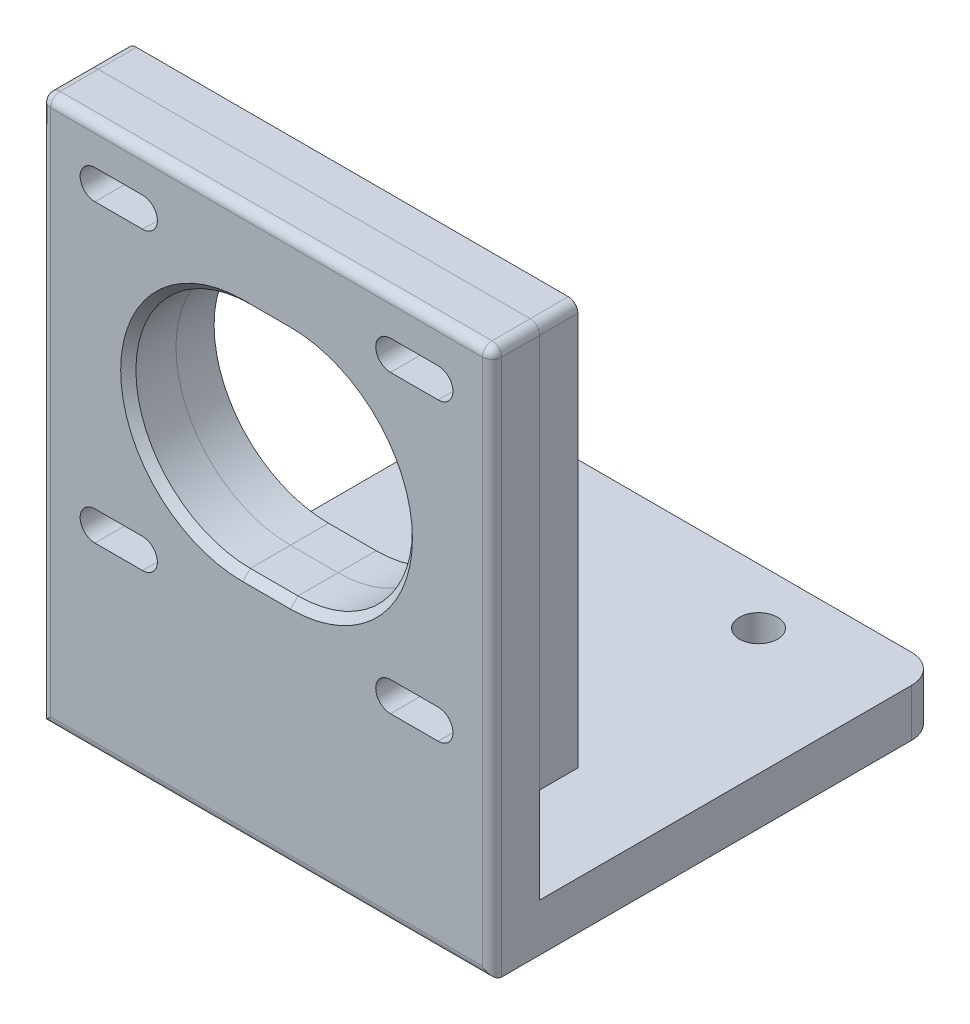
SolidWorks part; units mm, degrees
ref_plane "Front Plane" through (0, 0, 0) normal (0, 0, 1) x (1, 0, 0)
ref_plane "Top Plane" through (0, 0, 0) normal (0, 1, 0) x (1, 0, 0)
ref_plane "Right Plane" through (0, 0, 0) normal (1, 0, 0) x (0, 0, -1)
sketch "Sketch2" plane through (0, 0, 0) normal (1, 0, 0) x (0, 0, -1)
  line L0 (0, 0) -> (0, -47.3)
  line L4 (0, -47.3) -> (0, -52.3)
  line L5 (0, -52.3) -> (42, -52.3)
  line L6 (42, -52.3) -> (42, -57.3)
  line L7 (42, -57.3) -> (-5, -57.3)
  line L8 (-5, -57.3) -> (-5, 0)
  line L9 (-5, 0) -> (0, 0)
  dimension "D1" = 47.3
  dimension "D2" = 5
  dimension "D3" = 5
  dimension "D4" = 42
extrude "Boss-Extrude2" add sketch "Sketch2" along normal blind 47.3
sketch "Sketch3" plane through (0, 0, 5) normal (0, 0, 1) x (1, 0, 0)
  line L0 (21.15, -21.15) -> (26.15, -21.15) construction
  line L1 (21.15, -9.15) -> (26.15, -9.15)
  line L2 (21.15, -33.15) -> (26.15, -33.15)
  line L3 (0, -42.3) -> (47.3, -42.3) construction
  line L7 (0, 0) -> (0, -57.3) construction
  line L8 (5.65, -36.65) -> (10.65, -36.65) construction
  line L9 (5.65, -35.1) -> (10.65, -35.1)
  line L10 (5.65, -38.2) -> (10.65, -38.2)
  line L11 (47.3, 0) -> (47.3, -57.3) construction
  line L12 (47.3, 0) -> (0, 0) construction
  line L13 (23.65, -21.15) -> (50023.65, -21.15) construction
  line L16 (5.65, -7.2) -> (10.65, -7.2)
  line L19 (5.65, -4.1) -> (10.65, -4.1)
  line L22 (23.65, -42.3) -> (23.65, 0) construction
  line L23 (5.65, -5.65) -> (10.65, -5.65) construction
  line L24 (36.65, -7.2) -> (41.65, -7.2)
  line L25 (36.65, -4.1) -> (41.65, -4.1)
  line L26 (36.65, -5.65) -> (41.65, -5.65) construction
  line L27 (36.65, -38.2) -> (41.65, -38.2)
  line L28 (36.65, -35.1) -> (41.65, -35.1)
  line L29 (36.65, -36.65) -> (41.65, -36.65) construction
  arc A0 (21.15, -9.15) -> (21.15, -33.15) centre (21.15, -21.15) ccw
  arc A1 (26.15, -33.15) -> (26.15, -9.15) centre (26.15, -21.15) ccw
  arc A2 (5.65, -35.1) -> (5.65, -38.2) centre (5.65, -36.65) ccw
  arc A3 (10.65, -38.2) -> (10.65, -35.1) centre (10.65, -36.65) ccw
  arc A10 (5.65, -4.1) -> (5.65, -7.2) centre (5.65, -5.65) ccw
  arc A11 (10.65, -7.2) -> (10.65, -4.1) centre (10.65, -5.65) ccw
  arc A12 (36.65, -4.1) -> (36.65, -7.2) centre (36.65, -5.65) ccw
  arc A13 (41.65, -7.2) -> (41.65, -4.1) centre (41.65, -5.65) ccw
  arc A14 (36.65, -35.1) -> (36.65, -38.2) centre (36.65, -36.65) ccw
  arc A15 (41.65, -38.2) -> (41.65, -35.1) centre (41.65, -36.65) ccw
  point P2 (23.65, -21.15)
  point P15 (8.15, -36.65)
  point P30 (8.15, -5.65)
  point P37 (39.15, -5.65)
  point P44 (39.15, -36.65)
  dimension "D6" = 1.55
  dimension "D1" = 24
  dimension "D2" = 5
  dimension "D4" = 15.5
  dimension "D3" = 42.3
  dimension "D5" = 15.5
  dimension "D7" = 2
  dimension "D8" = 2
extrude "Cut-Extrude1" cut sketch "Sketch3" against normal up to next
fillet "Fillet1" radius 1 6 edges at (23.65, -57.3, 5) (47.3, -28.65, 5) (0, -28.65, 5) (23.65, 0, 5) (47.3, 0, 2.5) (0, 0, 2.5)
chamfer "Chamfer1" distance 0.8 angle 45 4 edges at (38.15, -21.15, 5) (23.65, -9.15, 5) (23.65, -33.15, 5) (9.15, -21.15, 5)
fillet "Fillet2" radius 3 2 edges at (47.3, -54.8, -42) (0, -54.8, -42)
sketch "Sketch4" plane through (0, -52.3, 0) normal (0, 1, 0) x (1, 0, 0)
  line L0 (9.65, 5) -> (37.65, 33) construction
  line L1 (44.3, 42) -> (3, 42) construction
  line L2 (9.65, 5) -> (37.65, 33) construction
  line L3 (9.65, 5) -> (34.0834, 36.161) construction
  circle A0 centre (9.65, 5) radius 2
  circle A1 centre (37.65, 33) radius 2 construction
  circle A2 centre (34.0834, 36.161) radius 2
  point P4 (23.65, 19)
  point P7 (23.65, 42)
  dimension "D1" = 4
  dimension "D2" = 4
  dimension "D4" = 28
  dimension "D5" = 28
  dimension "D3" = 5
  dimension "D7" = 6.9
  dimension "D6" = 2
extrude "Cut-Extrude2" cut sketch "Sketch4" against normal up to next
sketch "Sketch5" plane through (0, 0, 0) normal (0, 0, -1) x (-1, 0, 0)
  line L0 (-21.15, -9.15) -> (-26.15, -9.15) construction
  line L1 (-26.15, -33.15) -> (-21.15, -33.15) construction
  line L2 (-21.15, -9.15) -> (-26.15, -9.15)
  line L3 (-26.15, -33.15) -> (-21.15, -33.15)
  line L4 (-41.65, -7.2) -> (-36.65, -7.2) construction
  line L5 (-36.65, -4.1) -> (-41.65, -4.1) construction
  line L6 (-41.65, -38.2) -> (-36.65, -38.2) construction
  line L7 (-36.65, -35.1) -> (-41.65, -35.1) construction
  line L8 (-10.65, -38.2) -> (-5.65, -38.2) construction
  line L9 (-5.65, -35.1) -> (-10.65, -35.1) construction
  line L10 (-5.65, -4.1) -> (-10.65, -4.1) construction
  line L11 (-10.65, -7.2) -> (-5.65, -7.2) construction
  line L12 (-41.65, -7.2) -> (-36.65, -7.2)
  line L13 (-36.65, -4.1) -> (-41.65, -4.1)
  line L14 (-41.65, -38.2) -> (-36.65, -38.2)
  line L15 (-36.65, -35.1) -> (-41.65, -35.1)
  line L16 (-10.65, -38.2) -> (-5.65, -38.2)
  line L17 (-5.65, -35.1) -> (-10.65, -35.1)
  line L18 (-5.65, -4.1) -> (-10.65, -4.1)
  line L19 (-10.65, -7.2) -> (-5.65, -7.2)
  line L20 (-46.3, 0) -> (-1, 0) construction
  line L21 (-46.3, 0) -> (-1, 0)
  line L22 (0, -1) -> (0, -42.3)
  line L23 (0, -52.3) -> (0, -1) construction
  line L24 (0, -42.3) -> (-47.3, -42.3)
  line L25 (-47.3, -52.3) -> (-47.3, -1) construction
  line L26 (-47.3, -42.3) -> (-47.3, -1)
  arc A0 (-21.15, -33.15) -> (-21.15, -9.15) centre (-21.15, -21.15) ccw construction
  arc A1 (-26.15, -9.15) -> (-26.15, -33.15) centre (-26.15, -21.15) ccw construction
  arc A2 (-21.15, -33.15) -> (-21.15, -9.15) centre (-21.15, -21.15) ccw
  arc A3 (-26.15, -9.15) -> (-26.15, -33.15) centre (-26.15, -21.15) ccw
  arc A4 (-41.65, -4.1) -> (-41.65, -7.2) centre (-41.65, -5.65) ccw construction
  arc A5 (-36.65, -7.2) -> (-36.65, -4.1) centre (-36.65, -5.65) ccw construction
  arc A6 (-41.65, -35.1) -> (-41.65, -38.2) centre (-41.65, -36.65) ccw construction
  arc A7 (-36.65, -38.2) -> (-36.65, -35.1) centre (-36.65, -36.65) ccw construction
  arc A8 (-5.65, -38.2) -> (-5.65, -35.1) centre (-5.65, -36.65) ccw construction
  arc A9 (-10.65, -35.1) -> (-10.65, -38.2) centre (-10.65, -36.65) ccw construction
  arc A10 (-10.65, -4.1) -> (-10.65, -7.2) centre (-10.65, -5.65) ccw construction
  arc A11 (-5.65, -7.2) -> (-5.65, -4.1) centre (-5.65, -5.65) ccw construction
  arc A12 (-41.65, -4.1) -> (-41.65, -7.2) centre (-41.65, -5.65) ccw
  arc A13 (-36.65, -7.2) -> (-36.65, -4.1) centre (-36.65, -5.65) ccw
  arc A14 (-41.65, -35.1) -> (-41.65, -38.2) centre (-41.65, -36.65) ccw
  arc A15 (-36.65, -38.2) -> (-36.65, -35.1) centre (-36.65, -36.65) ccw
  arc A16 (-5.65, -38.2) -> (-5.65, -35.1) centre (-5.65, -36.65) ccw
  arc A17 (-10.65, -35.1) -> (-10.65, -38.2) centre (-10.65, -36.65) ccw
  arc A18 (-10.65, -4.1) -> (-10.65, -7.2) centre (-10.65, -5.65) ccw
  arc A19 (-5.65, -7.2) -> (-5.65, -4.1) centre (-5.65, -5.65) ccw
  arc A20 (-46.3, 0) -> (-47.3, -1) centre (-46.3, -1) ccw construction
  arc A21 (0, -1) -> (-1, 0) centre (-1, -1) ccw construction
  arc A22 (-46.3, 0) -> (-47.3, -1) centre (-46.3, -1) ccw
  arc A23 (0, -1) -> (-1, 0) centre (-1, -1) ccw
  dimension "D1" = 42.3
extrude "Boss-Extrude3" add sketch "Sketch5" along normal blind 4 separate body
equation "\"D5@Sketch3\"=\"D4@Sketch3\""
equation "\"D2@Sketch4\"=\"D1@Sketch4\""
equation "\"D5@Sketch4\"=\"D4@Sketch4\""
